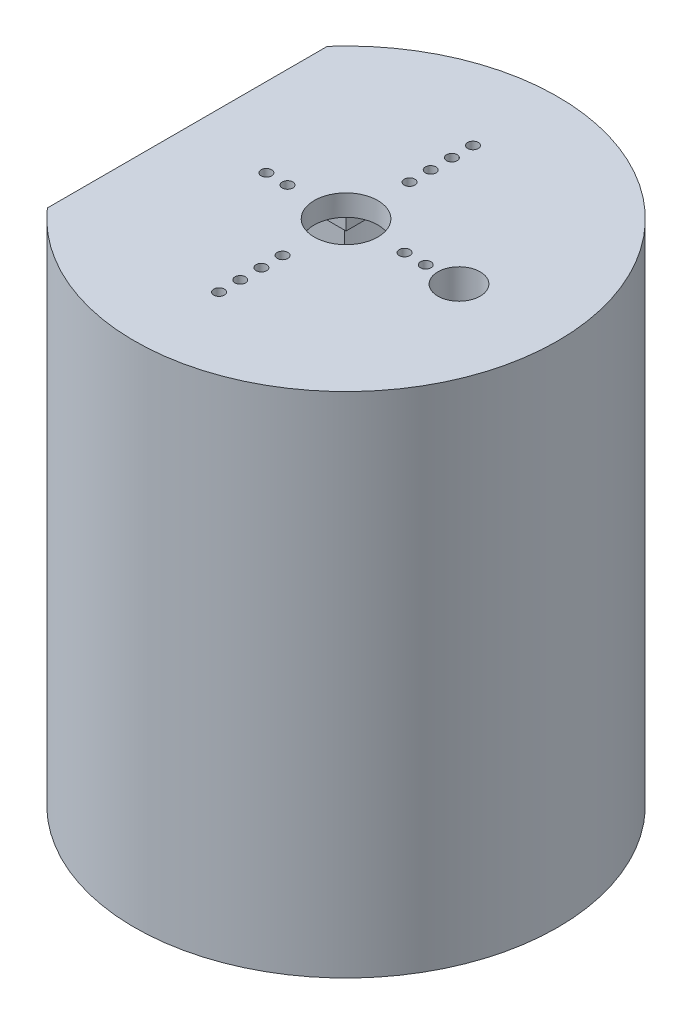
SolidWorks part; units mm, degrees
ref_plane "前视基准面" through (0, 0, 0) normal (0, 0, 1) x (1, 0, 0)
ref_plane "上视基准面" through (0, 0, 0) normal (0, 1, 0) x (1, 0, 0)
ref_plane "右视基准面" through (0, 0, 0) normal (1, 0, 0) x (0, 0, -1)
sketch "草图1" plane through (0, 0, 0) normal (0, 1, 0) x (1, 0, 0)
  circle A0 centre (0, 0) radius 20
  circle A1 centre (0, 0) radius 16
  dimension "D1" = 40
  dimension "D2" = 4
extrude "凸台-拉伸1" add sketch "草图1" along normal blind 40
sketch "草图2" plane through (0, 40, 0) normal (0, 1, 0) x (1, 0, 0)
  circle A0 centre (0, 0) radius 20
extrude "凸台-拉伸2" add sketch "草图2" along normal blind 4
sketch "草图3" plane through (0, 44, 0) normal (0, 1, 0) x (1, 0, 0)
  circle A0 centre (0, 0) radius 3
  dimension "D1" = 6
extrude "切除-拉伸1" cut sketch "草图3" against normal blind 4
sketch "草图5" plane through (0, 40, 0) normal (0, -1, 0) x (1, 0, 0)
  line L0 (0, 10) -> (0, -10) construction
  line L1 (3, 10) -> (3, -10)
  line L2 (-3, 10) -> (-3, -10)
  arc A0 (3, 10) -> (-3, 10) centre (0, 10) ccw
  arc A1 (-3, -10) -> (3, -10) centre (0, -10) ccw
  point P3 (0, 0)
  dimension "D1" = 3
  dimension "D2" = 20
  dimension "D3" = 10
extrude "切除-拉伸2" cut sketch "草图5" against normal blind 2
sketch "草图7" plane through (0, 0, 0) normal (0, -1, 0) x (1, 0, 0)
  circle A0 centre (0, 0) radius 20
extrude "凸台-拉伸3" add sketch "草图7" along normal blind 4
sketch "草图8" plane through (0, -4, 0) normal (0, -1, 0) x (1, 0, 0)
  circle A0 centre (0, 0) radius 1.5
  dimension "D1" = 3
extrude "切除-拉伸4" cut sketch "草图8" against normal blind 6
sketch "草图10" plane through (0, 44, 0) normal (0, 1, 0) x (1, 0, 0)
  line L1 (-25, -15) -> (-15, -15)
  line L2 (-25, -15) -> (-25, 15)
  line L3 (-25, 15) -> (-15, 15)
  line L4 (-15, -15) -> (-15, 15)
  line L5 (-25, -15) -> (-15, 15) construction
  line L6 (-25, 15) -> (-15, -15) construction
  circle A0 centre (0, 0) radius 20 construction
  point P0 (-20, 0)
  dimension "D1" = 30
  dimension "D2" = 10
extrude "切除-拉伸6" cut sketch "草图10" against normal blind 48
sketch "草图11" plane through (-15, 0, 0) normal (-1, 0, 0) x (0, 0, 1)
  line L0 (-13.2288, 44) -> (24122.9804, -43744.6219) construction
  line L1 (13.2288, 44) -> (-24122.9804, -43744.6219) construction
  line L2 (13.2288, 44) -> (-13.2288, 44) construction
  line L3 (11.2288, 0) -> (-11.2288, 0)
  line L4 (11.2288, 0) -> (11.2288, 40)
  line L5 (11.2288, 40) -> (-11.2288, 40)
  line L6 (-11.2288, 0) -> (-11.2288, 40)
  line L7 (11.2288, 0) -> (-11.2288, 40) construction
  line L8 (11.2288, 40) -> (-11.2288, 0) construction
  line L9 (-13.2288, -4) -> (-13.2288, 44) construction
  point P8 (0, 20)
  point P13 (0, 0)
  point P14 (0, 0)
  dimension "D1" = 4
  dimension "D2" = 2
extrude "切除-拉伸9" cut sketch "草图11" against normal blind 25
sketch "草图12" plane through (0, 0, 0) normal (0, 1, 0) x (1, 0, 0)
  line L0 (-15, 11.2288) -> (-15, -11.2288) construction
  line L1 (0, 2.8868) -> (-2.5, 1.4434)
  line L2 (-2.5, 1.4434) -> (-2.5, -1.4434)
  line L3 (-2.5, -1.4434) -> (0, -2.8868)
  line L4 (0, -2.8868) -> (2.5, -1.4434)
  line L5 (2.5, -1.4434) -> (2.5, 1.4434)
  line L6 (2.5, 1.4434) -> (0, 2.8868)
  circle A0 centre (0, 0) radius 2.5 construction
  dimension "D1" = 5
extrude "切除-拉伸10" cut sketch "草图12" against normal blind 2
sketch "草图14" plane through (0, 40, 0) normal (0, -1, 0) x (1, 0, 0)
  circle A0 centre (10.6745, 0) radius 2
  dimension "D1" = 4
extrude "切除-拉伸11" cut sketch "草图14" against normal blind 4
sketch "草图15" plane through (0, 40, 0) normal (0, -1, 0) x (1, 0, 0)
  line L0 (-7, 0) -> (5.5284, 0) construction
  line L1 (-7, 3) -> (5.5284, 3)
  line L2 (-7, -3) -> (5.5284, -3)
  arc A0 (-7, 3) -> (-7, -3) centre (-7, 0) ccw
  arc A1 (5.5284, -3) -> (5.5284, 3) centre (5.5284, 0) ccw
  point P3 (-0.7358, 0)
  dimension "D1" = 3
  dimension "D2" = 10
extrude "切除-拉伸12" cut sketch "草图15" against normal blind 2
sketch "草图16" plane through (0, 42, 0) normal (0, -1, 0) x (1, 0, 0)
  line L0 (0, 0) -> (0, -50000) construction
  line L1 (0, 0) -> (50000, 0) construction
  arc A0 (-3, -10) -> (3, -10) centre (0, -10) ccw construction
  arc A1 (5.5284, -3) -> (5.5284, 3) centre (5.5284, 0) ccw construction
  circle A2 centre (0, 12) radius 0.5
  circle A3 centre (0, 10) radius 0.5
  circle A4 centre (0, 8) radius 0.5
  circle A5 centre (0, 6) radius 0.5
  circle A6 centre (-7.5313, 0) radius 0.5
  circle A7 centre (-5.5313, 0) radius 0.5
  circle A9 centre (5.5313, 0) radius 0.5
  circle A10 centre (7.5313, 0) radius 0.5
  circle A11 centre (0, -6) radius 0.5
  circle A12 centre (0, -8) radius 0.5
  circle A13 centre (0, -10) radius 0.5
  circle A14 centre (0, -12) radius 0.5
  point P6 (0, -13)
  point P13 (8.5284, 0)
  dimension "D1" = 1
  dimension "D2" = 2
  dimension "D3" = 2
  dimension "D4" = 2
  dimension "D5" = 2
extrude "切除-拉伸13" cut sketch "草图16" against normal through all
